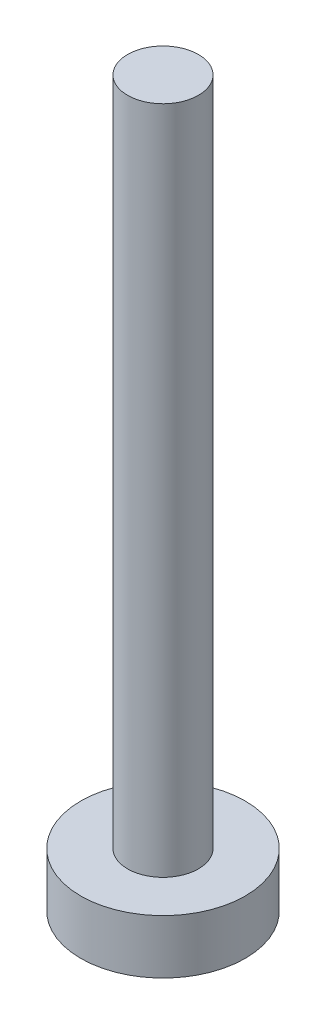
SolidWorks part; units mm, degrees
ref_plane "Front Plane" through (0, 0, 0) normal (0, 0, 1) x (1, 0, 0)
ref_plane "Top Plane" through (0, 0, 0) normal (0, 1, 0) x (1, 0, 0)
ref_plane "Right Plane" through (0, 0, 0) normal (1, 0, 0) x (0, 0, -1)
sketch "Sketch1" plane through (0, 0, 0) normal (0, 1, 0) x (1, 0, 0)
  circle A0 centre (0, 0) radius 1.46
  dimension "D1" = 2.92
extrude "Boss-Extrude1" add sketch "Sketch1" along normal blind 0.96
sketch "Sketch2" plane through (0, 0, 0) normal (0, -1, 0) x (1, 0, 0)
  circle A0 centre (0, 0) radius 0.6283
extrude "Boss-Extrude2" add sketch "Sketch2" against normal blind 12.85
